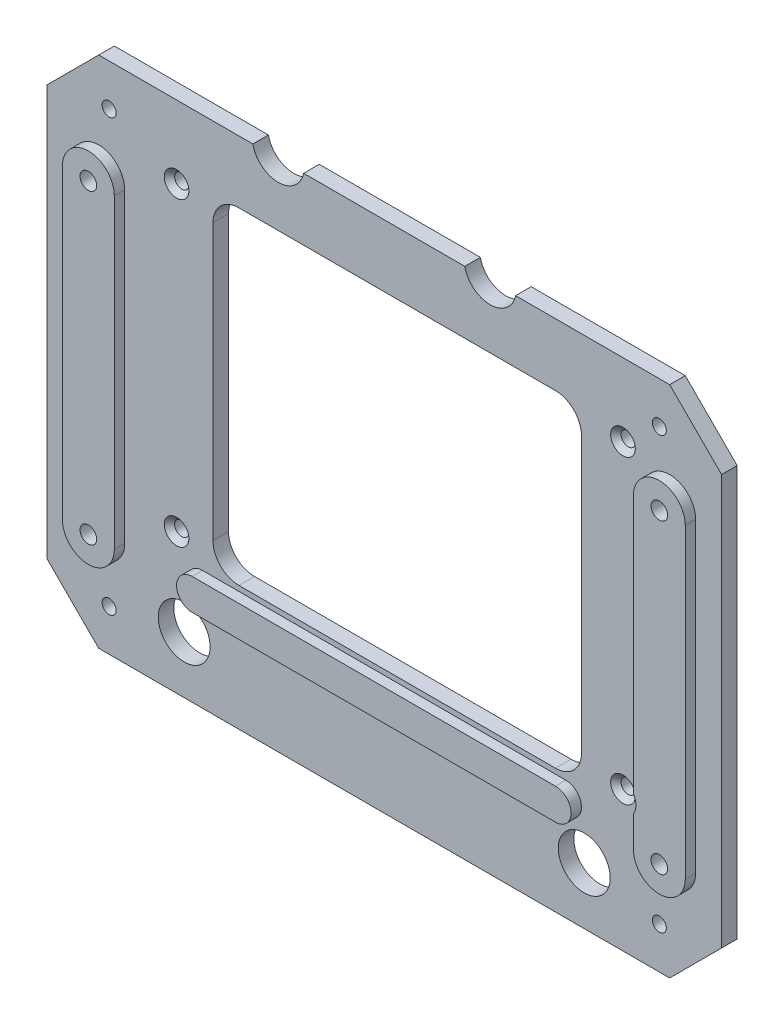
SolidWorks part; units mm, degrees
ref_plane "Front Plane" through (0, 0, 0) normal (0, 0, 1) x (1, 0, 0)
ref_plane "Top Plane" through (0, 0, 0) normal (0, 1, 0) x (1, 0, 0)
ref_plane "Right Plane" through (0, 0, 0) normal (1, 0, 0) x (0, 0, -1)
sketch "Sketch1" plane through (0, 0, 0) normal (0, 0, 1) x (1, 0, 0)
  line L0 (3.4, 62) -> (-95.4, 62) construction
  line L1 (9, 72) -> (-20.6915, 72)
  line L2 (19, 62) -> (19, -17)
  line L3 (9, -27) -> (-101, -27)
  line L4 (-111, 62) -> (-111, -17)
  line L5 (4, -16.4) -> (4, 61.4) construction
  line L6 (-96, 61.4) -> (-96, -16.4) construction
  line L7 (-85.855, -17) -> (-80.9, -17) construction
  line L8 (-30.4764, 72) -> (-61.5236, 72)
  line L9 (-71.3085, 72) -> (-101, 72)
  line L10 (19, 62) -> (9, 72)
  line L11 (19, -17) -> (9, -27)
  line L12 (-101, -27) -> (-111, -17)
  line L13 (-101, 72) -> (-111, 62)
  circle A1 centre (-86, 0) radius 1.375 construction
  circle A2 centre (-86, 58) radius 1.375 construction
  circle A3 centre (0, 0) radius 1.375 construction
  circle A4 centre (0, 58) radius 1.375 construction
  circle A5 centre (-86, 0) radius 1.375
  circle A6 centre (-86, 58) radius 1.375
  circle A7 centre (0, 0) radius 1.375
  circle A8 centre (0, 58) radius 1.375
  circle A9 centre (-7.4627, -16.0373) radius 5
  circle A10 centre (-84.5373, -16.0373) radius 5
  arc A11 (-30.4764, 72) -> (-20.6915, 72) centre (-25.5839, 73.0315) ccw
  arc A12 (-71.3085, 72) -> (-61.5236, 72) centre (-66.4161, 73.0315) ccw
  point P0 (19, 72)
  point P1 (-111, -27)
  point P2 (19, -27)
  point P3 (-111, 72)
  dimension "D1" = 10
  dimension "D5" = 10
  dimension "D2" = 15
  dimension "D3" = 15
  dimension "D4" = 10
extrude "Extrude1" add sketch "Sketch1" along normal blind 3
sketch "Sketch2" plane through (0, 0, 0) normal (0, 0, -1) x (-1, 0, 0)
  line L0 (30.4764, 72) -> (61.5236, 72) construction
  line L1 (13, 60) -> (74, 60)
  line L2 (8, 55) -> (8, 2)
  line L3 (13, -3) -> (74, -3)
  line L4 (79, 55) -> (79, 2)
  line L5 (101, -27) -> (-9, -27) construction
  line L6 (-19, -17) -> (-19, 62) construction
  line L7 (111, 62) -> (111, -17) construction
  line L8 (-9, 72) -> (20.6915, 72) construction
  line L9 (-9, 52) -> (101, 52) construction
  line L10 (-9, 52) -> (-9, -7) construction
  line L11 (-9, -7) -> (101, -7) construction
  line L12 (101, 52) -> (101, -7) construction
  arc A0 (74, 60) -> (79, 55) centre (74, 55) cw
  arc A1 (74, -3) -> (79, 2) centre (74, 2) ccw
  arc A2 (8, 2) -> (13, -3) centre (13, 2) ccw
  arc A3 (13, 60) -> (8, 55) centre (13, 55) ccw
  circle A4 centre (-9, 52) radius 1.6
  circle A5 centre (-9, -7) radius 1.6
  circle A6 centre (101, 52) radius 1.6
  circle A7 centre (101, -7) radius 1.6
  dimension "D5" = 5
  dimension "D10" = 3.2
  dimension "D1" = 12
  dimension "D2" = 24
  dimension "D3" = 27
  dimension "D4" = 32
  dimension "D6" = 10
  dimension "D7" = 10
  dimension "D8" = 20
  dimension "D9" = 20
extrude "Cut-Extrude1" cut sketch "Sketch2" against normal blind 3
sketch "Sketch3" plane through (0, 0, 3) normal (0, 0, 1) x (1, 0, 0)
  line L0 (4, -1.0689) -> (4, -7)
  line L2 (14, 52) -> (14, -7)
  line L4 (4, 52) -> (4, 2.2419)
  line L6 (-96, 52) -> (-96, -7)
  line L8 (-106, 52) -> (-106, -7)
  arc A0 (14, 52) -> (4, 52) centre (9, 52) ccw
  arc A1 (4, -7) -> (14, -7) centre (9, -7) ccw
  arc A2 (-96, 52) -> (-106, 52) centre (-101, 52) ccw
  arc A3 (-106, -7) -> (-96, -7) centre (-101, -7) ccw
  circle A4 centre (9, -7) radius 1.6 construction
  circle A5 centre (9, 52) radius 1.6 construction
  circle A6 centre (-101, -7) radius 1.6 construction
  circle A7 centre (-101, 52) radius 1.6 construction
  circle A8 centre (9, -7) radius 1.6
  circle A9 centre (9, 52) radius 1.6
  circle A10 centre (-101, -7) radius 1.6
  circle A11 centre (-101, 52) radius 1.6
  arc A14 (4, -1.0689) -> (4, 2.2419) centre (1.4981, 0.5865) ccw
  dimension "D1" = 10
  dimension "D2" = 6
extrude "Extrude2" add sketch "Sketch3" along normal blind 2
sketch "Sketch4" plane through (0, 0, 3) normal (0, 0, 1) x (1, 0, 0)
  line L0 (9, 52) -> (-101, 52) construction
  line L1 (9, -7) -> (-101, -7) construction
  line L5 (-11, -7) -> (-81, -7) construction
  line L6 (-11, -10) -> (-81, -10)
  line L7 (-11, -4) -> (-81, -4)
  line L8 (19, -17) -> (19, 62) construction
  line L9 (-111, 62) -> (-111, -17) construction
  arc A2 (-11, -10) -> (-11, -4) centre (-11, -7) ccw
  arc A3 (-81, -4) -> (-81, -10) centre (-81, -7) ccw
  point P15 (-46, -7)
  dimension "D6" = 3
  dimension "D1" = 30
  dimension "D4" = 30
extrude "Extrude3" add sketch "Sketch4" along normal blind 2
sketch "Sketch5" plane through (0, 0, 0) normal (0, 0, -1) x (-1, 0, 0)
  line L0 (-9, 72) -> (20.6915, 72) construction
  line L1 (-7, 64) -> (99, 64) construction
  line L2 (-7, 64) -> (-7, -19) construction
  line L3 (-7, -19) -> (99, -19) construction
  line L4 (99, 64) -> (99, -19) construction
  line L5 (-19, -17) -> (-19, 62) construction
  line L6 (111, 62) -> (111, -17) construction
  line L7 (101, -27) -> (-9, -27) construction
  circle A0 centre (-7, 64) radius 1.35
  circle A1 centre (99, 64) radius 1.35
  circle A2 centre (99, -19) radius 1.35
  circle A3 centre (-7, -19) radius 1.35
  dimension "D5" = 2.7
  dimension "D1" = 8
  dimension "D2" = 12
  dimension "D3" = 12
  dimension "D4" = 8
extrude "Cut-Extrude2" cut sketch "Sketch5" against normal blind 5
chamfer "Chamfer1" distance 1 angle 45 4 edges at (1.375, 0, 3) (-84.625, 0, 3) (1.375, 58, 3) (-84.625, 58, 3)
